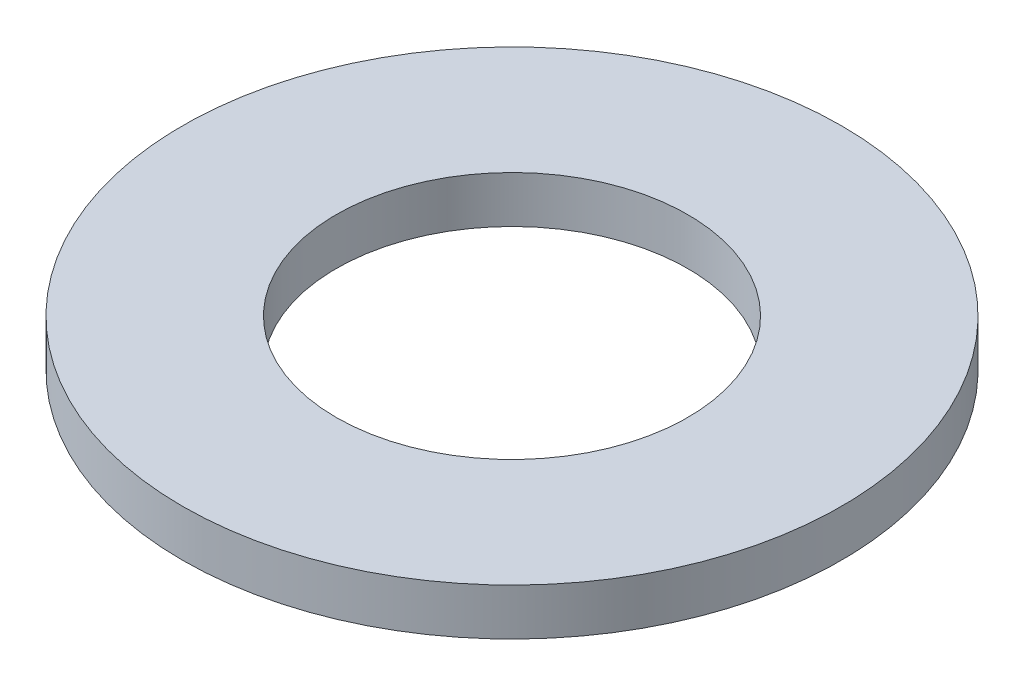
SolidWorks part; units mm, degrees
material "Alloy Steel"
ref_plane "Front Plane" through (0, 0, 0) normal (0, 0, 1) x (1, 0, 0)
ref_plane "Top Plane" through (0, 0, 0) normal (0, 1, 0) x (1, 0, 0)
ref_plane "Right Plane" through (0, 0, 0) normal (1, 0, 0) x (0, 0, -1)
sketch "Sketch1" plane through (0, 0, 0) normal (0, 1, 0) x (1, 0, 0)
  circle A0 centre (0, 0) radius 20
  circle A1 centre (0, 0) radius 37.5
  dimension "D1" = 40
  dimension "D2" = 75
extrude "Boss-Extrude1" add sketch "Sketch1" along normal blind 5.32
